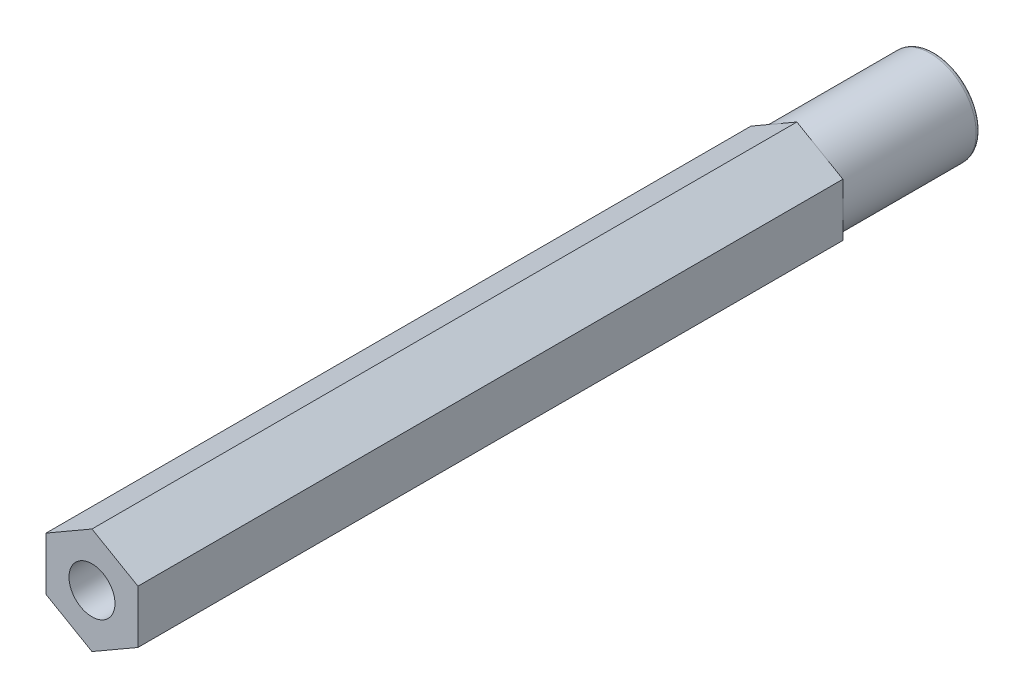
SolidWorks part; units mm, degrees
ref_plane "Front Plane" through (0, 0, 0) normal (0, 0, 1) x (1, 0, 0)
ref_plane "Top Plane" through (0, 0, 0) normal (0, 1, 0) x (1, 0, 0)
ref_plane "Right Plane" through (0, 0, 0) normal (1, 0, 0) x (0, 0, -1)
sketch "Sketch1" plane through (0, 0, 0) normal (0, 0, 1) x (1, 0, 0)
  line L1 (0, 1.1547) -> (-1, 0.5774)
  line L2 (-1, 0.5774) -> (-1, -0.5774)
  line L3 (-1, -0.5774) -> (0, -1.1547)
  line L4 (0, -1.1547) -> (1, -0.5774)
  line L5 (1, -0.5774) -> (1, 0.5774)
  line L6 (1, 0.5774) -> (0, 1.1547)
  circle A0 centre (0, 0) radius 1 construction
  dimension "D1" = 2
extrude "Boss-Extrude1" add sketch "Sketch1" along normal blind 15.3333
sketch "Sketch2" plane through (0, 0, 15.3333) normal (0, 0, 1) x (1, 0, 0)
  circle A0 centre (0, 0) radius 0.5
  dimension "D1" = 1
extrude "Cut-Extrude1" cut sketch "Sketch2" against normal blind 2
sketch "Sketch3" plane through (0, 0, 0) normal (0, 0, -1) x (-1, 0, 0)
  circle A0 centre (0, 0) radius 1
  dimension "D1" = 2
extrude "Boss-Extrude2" add sketch "Sketch3" along normal blind 3
fillet "Fillet1" radius 0.1 1 edges at (-1, 0, -3)
